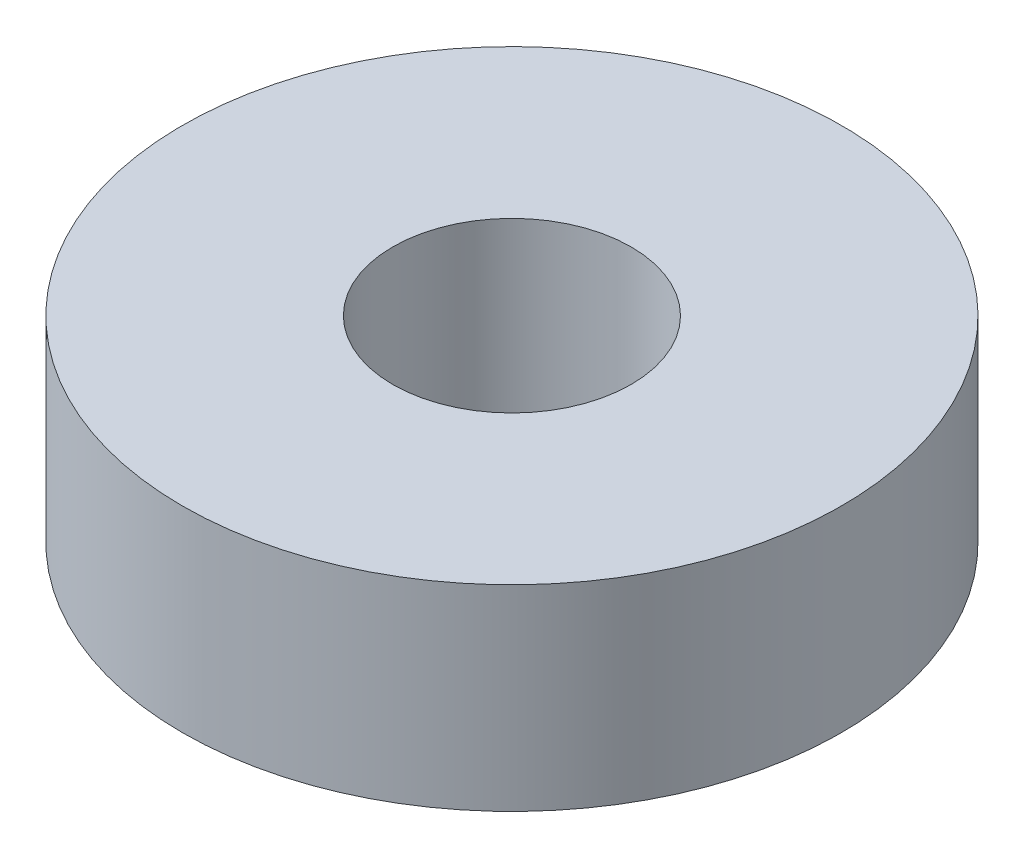
SolidWorks part; units mm, degrees
material "AISI 304"
ref_plane "前视基准面" through (0, 0, 0) normal (0, 0, 1) x (1, 0, 0)
ref_plane "上视基准面" through (0, 0, 0) normal (0, 1, 0) x (1, 0, 0)
ref_plane "右视基准面" through (0, 0, 0) normal (1, 0, 0) x (0, 0, -1)
sketch "草图1" plane through (0, 0, 0) normal (0, 1, 0) x (1, 0, 0)
  circle A0 centre (0, 0) radius 23.5
  circle A1 centre (0, 0) radius 8.5
  dimension "D1" = 47
  dimension "D2" = 17
extrude "凸台-拉伸1" add sketch "草图1" along normal blind 14
